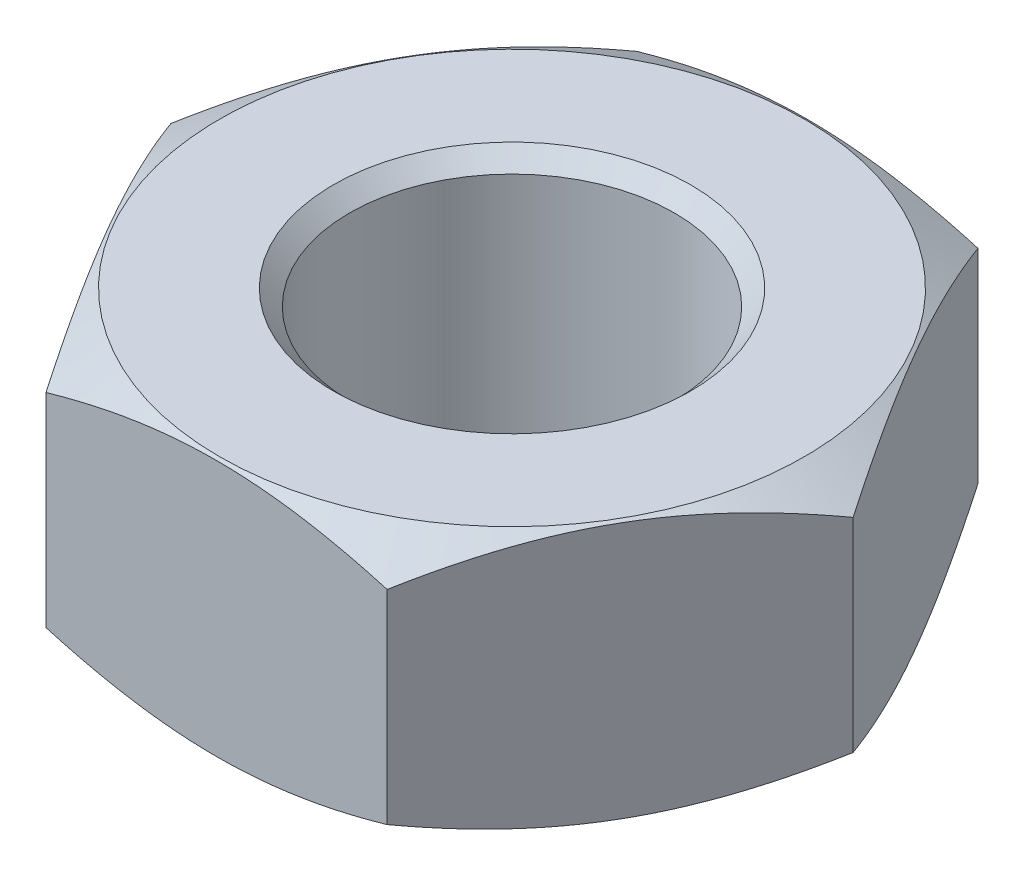
SolidWorks part; units mm, degrees
ref_plane "Спереди" through (0, 0, 0) normal (0, 0, 1) x (1, 0, 0)
ref_plane "Сверху" through (0, 0, 0) normal (0, 1, 0) x (1, 0, 0)
ref_plane "Справа" through (0, 0, 0) normal (1, 0, 0) x (0, 0, -1)
sketch "Эскиз1" plane through (0, 0, 0) normal (0, 1, 0) x (1, 0, 0)
  line L0 (-1.05, 1.8187) -> (1.05, 1.8187)
  line L1 (1.05, 1.8187) -> (2.1, 0)
  line L2 (2.1, 0) -> (1.05, -1.8187)
  line L3 (1.05, -1.8187) -> (-1.05, -1.8187)
  line L4 (-1.05, -1.8187) -> (-2.1, 0)
  line L5 (-2.1, 0) -> (-1.05, 1.8187)
  dimension "D1" = 2.1
  dimension "D2" = 120
  dimension "D3" = 120
  dimension "D4" = 120
  dimension "D5" = 1.8187
  dimension "D6" = 1.8187
  dimension "D7" = 1.8187
  dimension "D8" = 1.8187
  dimension "D9" = 1.8187
  dimension "D10" = 120
extrude "Вытянуть1" add sketch "Эскиз1" against normal blind 1.6
sketch "Эскиз2" plane through (0, 0, 0) normal (0, 1, 0) x (-1, 0, 0)
  circle A0 centre (0, 0) radius 1
  dimension "D1" = 2
extrude "Вырез-Вытянуть1" cut sketch "Эскиз2" against normal blind 1.6
chamfer "Фаска1" distance 0.1 angle 45 2 edges at (0, 0, 1) (0, -1.6, 1)
sketch "Эскиз3" plane through (0, 0, 0) normal (0, 0, 1) x (1, 0, 0)
  line L0 (-1.8, 0) -> (-2.1, -0.1732)
  line L1 (-2.1, 0) -> (-1.05, 0) construction
  line L2 (-2.1, -0.1732) -> (-2.1, 0)
  line L3 (-2.1, 0) -> (-1.8, 0)
  line L4 (-2.1, -1.6) -> (-2.1, -1.4268)
  line L5 (-2.1, -1.6) -> (-2.1, 0) construction
  line L6 (-2.1, -1.4268) -> (-1.8, -1.6)
  line L7 (-2.1, -1.6) -> (-1.05, -1.6) construction
  line L8 (-1.8, -1.6) -> (-2.1, -1.6)
  line L9 (-1.8, 0) -> (-1.8, -1.6) construction
  line L10 (0, 0) -> (0, -1.6) construction
  line L11 (-1.05, 0) -> (1.05, 0) construction
  line L12 (-1.05, -1.6) -> (1.05, -1.6) construction
  dimension "D1" = 1.8
  dimension "D2" = 30
  dimension "D3" = 30
revolve "Вырез-Повернуть1" cut sketch "Эскиз3" angle 360 about L10
